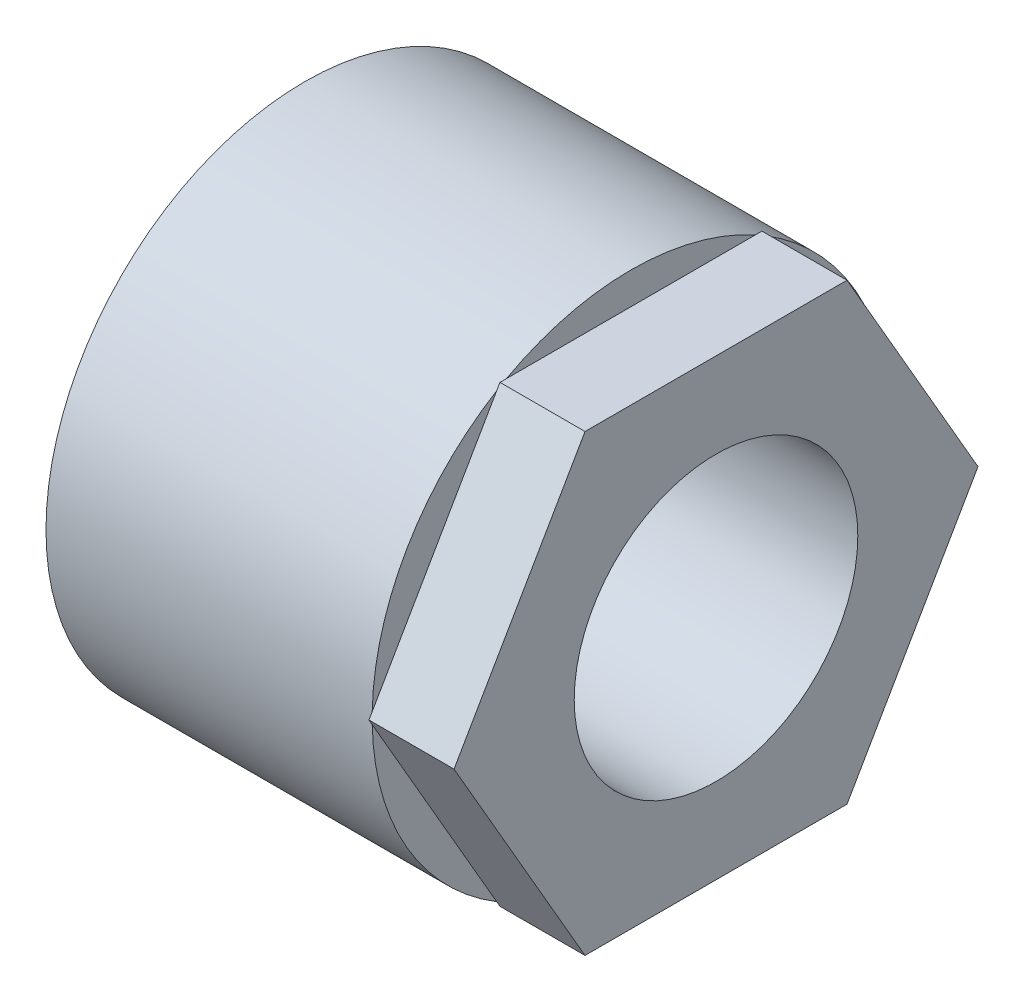
SolidWorks part; units mm, degrees
ref_plane "前视基准面" through (0, 0, 0) normal (0, 0, 1) x (1, 0, 0)
ref_plane "上视基准面" through (0, 0, 0) normal (0, 1, 0) x (1, 0, 0)
ref_plane "右视基准面" through (0, 0, 0) normal (1, 0, 0) x (0, 0, -1)
other "Configuration Table"
sketch "草图1" plane through (0, 0, 0) normal (0, 0, 1) x (1, 0, 0)
  line L0 (-5, 0) -> (28, 0) construction
  line L1 (0, 10) -> (0, 18.25)
  line L2 (0, 18.25) -> (23, 18.25)
  line L3 (23, 18.25) -> (23, 10)
  line L4 (23, 10) -> (0, 10)
revolve "01_SLEEVE" add sketch "草图1" angle 360 about L0
ref_plane "P_02_HEX" through (23, 0, 0) normal (1, 0, 0) x (0, 0, -1)
sketch "草图2" plane through (23, 0, 0) normal (1, 0, 0) x (0, 0, -1)
  line L1 (18.4752, 0) -> (9.2376, 16)
  line L2 (9.2376, 16) -> (-9.2376, 16)
  line L3 (-9.2376, 16) -> (-18.4752, 0)
  line L4 (-18.4752, 0) -> (-9.2376, -16)
  line L5 (-9.2376, -16) -> (9.2376, -16)
  line L6 (9.2376, -16) -> (18.4752, 0)
  circle A0 centre (0, 0) radius 16 construction
  circle A1 centre (0, 0) radius 10
extrude "02_HEX" add sketch "草图2" along normal blind 6
